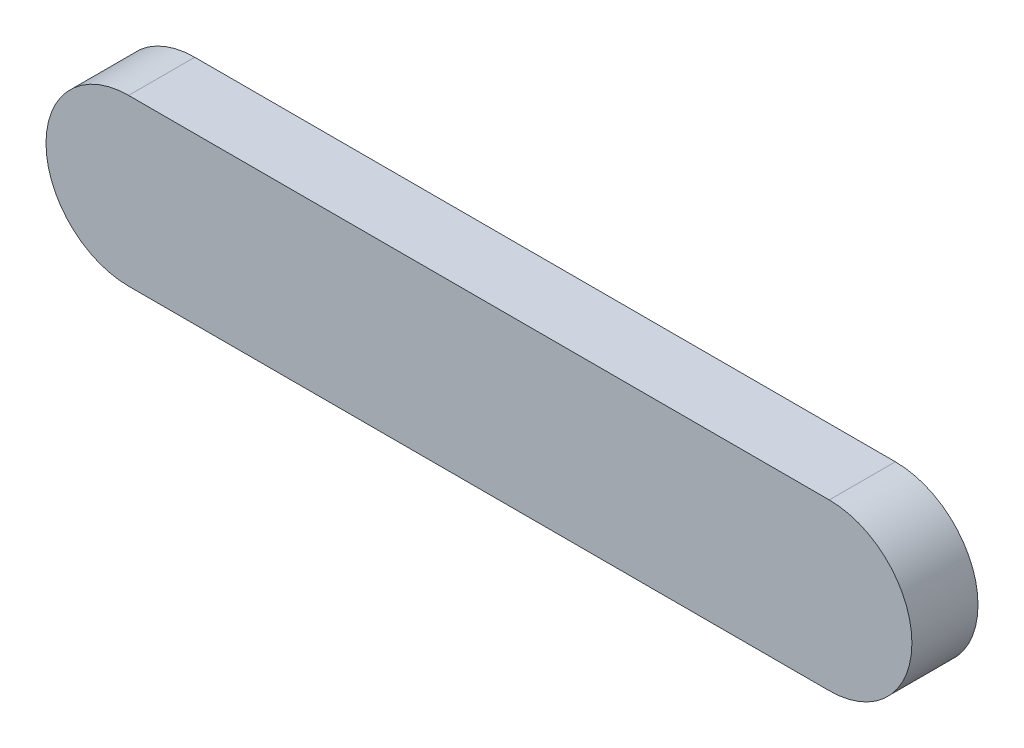
SolidWorks part; units mm, degrees
ref_plane "前视基准面" through (0, 0, 0) normal (0, 0, 1) x (1, 0, 0)
ref_plane "上视基准面" through (0, 0, 0) normal (0, 1, 0) x (1, 0, 0)
ref_plane "右视基准面" through (0, 0, 0) normal (1, 0, 0) x (0, 0, -1)
sketch "草图1" plane through (0, 0, 0) normal (0, 0, 1) x (1, 0, 0)
  line L0 (0, 0) -> (212, 0) construction
  line L1 (0, 25) -> (212, 25)
  line L2 (0, -25) -> (212, -25)
  arc A0 (0, 25) -> (0, -25) centre (0, 0) ccw
  arc A1 (212, -25) -> (212, 25) centre (212, 0) ccw
  point P3 (106, 0)
  dimension "D2" = 25
  dimension "D1" = 212
extrude "凸台-拉伸1" add sketch "草图1" along normal blind 20
